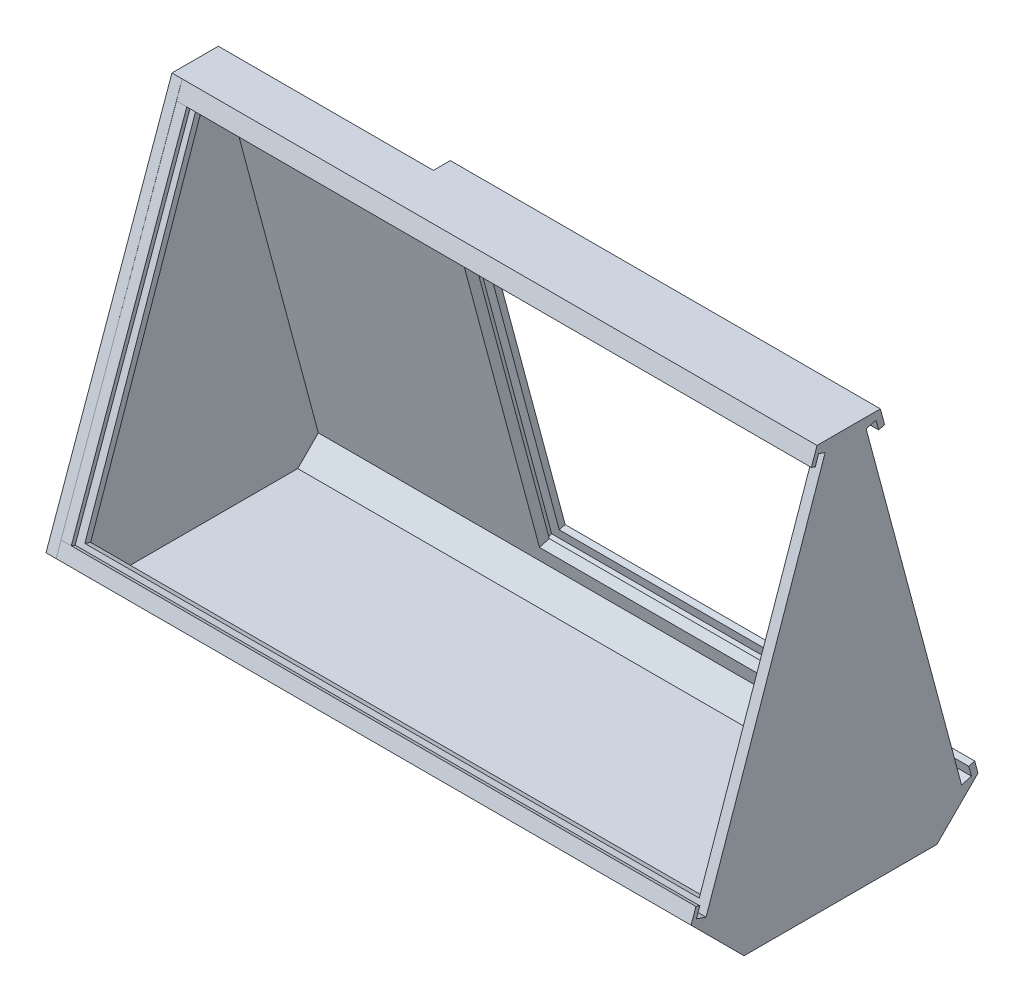
SolidWorks part; units mm, degrees
ref_plane "Front Plane" through (0, 0, 0) normal (0, 0, 1) x (1, 0, 0)
ref_plane "Top Plane" through (0, 0, 0) normal (0, 1, 0) x (1, 0, 0)
ref_plane "Right Plane" through (0, 0, 0) normal (1, 0, 0) x (0, 0, -1)
sketch3d "3DSketch1"
  line L0 (0, 1.3322, 65.6307) -> (0, 1.3322, -48.6693)
  line L1 (0, 19.2927, -66.6298) -> (0, 240.1033, -7.4638)
  line L2 (0, 240.1033, 17.9362) -> (0, 27.5025, 91.801)
  line L3 (0, 1.3322, 65.6307) -> (0, 27.5025, 91.801)
  line L4 (0, 240.1033, 17.9362) -> (0, 240.1033, -7.4638)
  line L5 (0, 19.2927, -66.6298) -> (0, 1.3322, -48.6693)
  point P0 (0, 152.3034, 238.9566)
  dimension "D1" = 25.4
  dimension "D2" = 228.6
  dimension "D3" = 75
  dimension "D4" = 45
  dimension "D5" = 45
  dimension "D6" = 114.3
  dimension "D7" = 225.0669
  dimension "D8" = 25.4
extrude "Boss-Extrude2" add sketch "3DSketch1" along direction (1, 0, 0) on the side of the normal blind 6.35
sketch "Sketch2" plane through (-6.35, 0, 0) normal (-1, 0, 0) x (0, 0, 1)
  line L0 (-61.4451, 14.1079) -> (-48.6693, 1.3322)
  line L1 (-48.6693, 1.3322) -> (65.6307, 1.3322)
  line L2 (65.6307, 1.3322) -> (88.8076, 24.5091)
  line L3 (-71.1199, 27.0698) -> (-74.8001, 28.0559)
  line L4 (-76.8232, 20.5058) -> (-51.2996, -5.0178)
  line L5 (-51.2996, -5.0178) -> (68.261, -5.0178)
  line L6 (68.261, -5.0178) -> (101.1012, 27.8224)
  line L7 (65.6307, 1.3322) -> (91.801, 27.5025) construction
  line L8 (-71.1199, 27.0698) -> (-72.7634, 20.9362)
  line L9 (91.801, 27.5025) -> (97.7993, 29.5865)
  line L10 (-7.4638, 240.1033) -> (-66.6298, 19.2927) construction
  line L11 (-66.6298, 19.2927) -> (-72.7634, 20.9362)
  line L12 (-74.8001, 28.0559) -> (-76.8232, 20.5058)
  line L13 (97.7993, 29.5865) -> (95.7153, 35.5848)
  line L14 (95.7153, 35.5848) -> (98.1146, 36.4184)
  line L15 (98.1146, 36.4184) -> (101.1012, 27.8224)
  line L17 (91.801, 27.5025) -> (17.9362, 240.1033) construction
  line L18 (-66.6298, 19.2927) -> (-64.9863, 25.4263)
  line L19 (-64.9863, 25.4263) -> (-58.8527, 23.7828)
  line L20 (-58.8527, 23.7828) -> (-61.4451, 14.1079)
  line L21 (91.801, 27.5025) -> (89.717, 33.5008)
  line L22 (89.717, 33.5008) -> (86.1181, 32.2504)
  line L23 (86.1181, 32.2504) -> (88.8076, 24.5091)
  dimension "D1" = 6.35
  dimension "D2" = 135
  dimension "D3" = 135
  dimension "D4" = 6.35
  dimension "D5" = 6.35
  dimension "D6" = 6.35
  dimension "D7" = 6.35
  dimension "D8" = 6.35
  dimension "D9" = 3.81
  dimension "D10" = 90
  dimension "D11" = 6.35
  dimension "D12" = 6.35
  dimension "D13" = 2.54
  dimension "D14" = 6.35
  dimension "D15" = 3.81
  dimension "D16" = 6.35
  dimension "D17" = 6.35
extrude "Boss-Extrude3" add sketch "Sketch2" against normal blind 6.35 and the other way blind 254
sketch "Sketch4" plane through (-6.35, 0, 0) normal (-1, 0, 0) x (0, 0, 1)
  line L0 (-0.8898, 240.1033) -> (13.9028, 240.1033)
  line L1 (17.9362, 240.1033) -> (20.0202, 234.105)
  line L2 (89.717, 33.5008) -> (17.9362, 240.1033) construction
  line L3 (16.4213, 232.8546) -> (13.9028, 240.1033)
  line L4 (-7.4638, 240.1033) -> (-13.5974, 241.7468)
  line L5 (-0.8898, 240.1033) -> (-2.9737, 232.3262)
  line L6 (-2.9737, 232.3262) -> (-9.1073, 233.9697)
  line L7 (-7.4638, 240.1033) -> (-64.9863, 25.4263) construction
  line L8 (-9.1073, 233.9697) -> (-7.4638, 240.1033)
  line L9 (16.4213, 232.8546) -> (20.0202, 234.105)
  line L10 (-13.5974, 241.7468) -> (-15.2409, 235.6132)
  line L11 (-15.2409, 235.6132) -> (-18.9211, 236.5993)
  line L12 (-18.9211, 236.5993) -> (-16.2807, 246.4533)
  line L13 (-16.2807, 246.4533) -> (23.001, 246.4533)
  line L14 (23.001, 246.4533) -> (26.5081, 236.3591)
  line L15 (26.5081, 236.3591) -> (24.1087, 235.5255)
  line L16 (24.1087, 235.5255) -> (22.0247, 241.5238)
  line L17 (22.0247, 241.5238) -> (17.9362, 240.1033)
  dimension "D1" = 180
  dimension "D2" = 90
  dimension "D3" = 3.81
  dimension "D4" = 6.35
  dimension "D5" = 6.35
  dimension "D6" = 6.35
  dimension "D7" = 3.81
  dimension "D8" = 6.35
  dimension "D9" = 6.35
  dimension "D10" = 6.35
  dimension "D11" = 90
  dimension "D12" = 270
  dimension "D13" = 6.35
  dimension "D14" = 2.54
  dimension "D15" = 6.35
  dimension "D16" = 3.81
extrude "Boss-Extrude4" add sketch "Sketch4" against normal blind 6.35 and the other way blind 254
sketch "Sketch5" plane through (-260.35, 0, 0) normal (-1, 0, 0) x (0, 0, 1)
  line L0 (-68.5276, 12.2102) -> (-51.2996, -5.0178)
  line L2 (-51.2996, -5.0178) -> (68.261, -5.0178)
  line L3 (68.261, -5.0178) -> (101.1012, 27.8224)
  line L4 (101.1012, 27.8224) -> (98.1146, 36.4184)
  line L5 (95.7153, 35.5848) -> (97.7993, 29.5865)
  line L6 (97.7993, 29.5865) -> (91.801, 27.5025)
  line L7 (91.801, 27.5025) -> (89.717, 33.5008)
  line L8 (89.717, 33.5008) -> (86.1181, 32.2504)
  line L9 (86.1181, 32.2504) -> (88.8076, 24.5091)
  line L10 (88.8076, 24.5091) -> (65.6307, 1.3322)
  line L11 (65.6307, 1.3322) -> (-48.6693, 1.3322)
  line L12 (-48.6693, 1.3322) -> (-61.4451, 14.1079)
  line L13 (-68.5276, 12.2102) -> (-5.7623, 246.4533)
  line L14 (-0.8898, 240.1033) -> (13.9028, 240.1033)
  line L15 (13.9028, 240.1033) -> (16.4213, 232.8546)
  line L16 (16.4213, 232.8546) -> (20.0202, 234.105)
  line L17 (20.0202, 234.105) -> (17.9362, 240.1033)
  line L18 (17.9362, 240.1033) -> (22.0247, 241.5238)
  line L19 (22.0247, 241.5238) -> (24.1087, 235.5255)
  line L20 (24.1087, 235.5255) -> (26.5081, 236.3591)
  line L21 (26.5081, 236.3591) -> (23.001, 246.4533)
  line L22 (23.001, 246.4533) -> (-5.7623, 246.4533)
  line L23 (-0.8898, 240.1033) -> (-61.4451, 14.1079)
  line L44 (-64.9863, 25.4263) -> (-66.6298, 19.2927)
  line L45 (-66.6298, 19.2927) -> (-72.7634, 20.9362)
  line L46 (-72.7634, 20.9362) -> (-71.1199, 27.0698)
  line L47 (-71.1199, 27.0698) -> (-74.8001, 28.0559)
  line L48 (-74.8001, 28.0559) -> (-76.8232, 20.5058)
  line L49 (-76.8232, 20.5058) -> (-51.2996, -5.0178)
  line L50 (-51.2996, -5.0178) -> (68.261, -5.0178)
  line L51 (68.261, -5.0178) -> (101.1012, 27.8224)
  line L52 (101.1012, 27.8224) -> (98.1146, 36.4184)
  line L53 (98.1146, 36.4184) -> (95.7153, 35.5848)
  line L54 (95.7153, 35.5848) -> (97.7993, 29.5865)
  line L55 (97.7993, 29.5865) -> (91.801, 27.5025)
  line L56 (91.801, 27.5025) -> (89.717, 33.5008)
  line L57 (89.717, 33.5008) -> (86.1181, 32.2504)
  line L58 (86.1181, 32.2504) -> (88.8076, 24.5091)
  line L59 (88.8076, 24.5091) -> (65.6307, 1.3322)
  line L60 (65.6307, 1.3322) -> (-48.6693, 1.3322)
  line L61 (-48.6693, 1.3322) -> (-61.4451, 14.1079)
  line L62 (-61.4451, 14.1079) -> (-58.8527, 23.7828)
  line L63 (-58.8527, 23.7828) -> (-64.9863, 25.4263)
  line L73 (98.1146, 36.4184) -> (95.7153, 35.5848)
  dimension "D1" = 0
extrude "Boss-Extrude5" add sketch "Sketch5" along normal blind 133.35
sketch "Sketch7" plane through (-260.35, 0, 0) normal (-1, 0, 0) x (0, 0, 1)
  line L0 (-16.2807, 246.4533) -> (-76.8232, 20.5058)
  line L1 (-76.8232, 20.5058) -> (-68.5276, 12.2102)
  line L2 (-68.5276, 12.2102) -> (-5.7623, 246.4533)
  line L3 (-5.7623, 246.4533) -> (-16.2807, 246.4533)
extrude "Boss-Extrude6" add sketch "Sketch7" along normal blind 6.35
sketch "Sketch9" plane through (-260.35, 0, 0) normal (1, 0, 0) x (0, 0, -1)
  line L0 (15.2409, 235.6132) -> (71.1199, 27.0698)
  line L1 (71.1199, 27.0698) -> (74.8001, 28.0559)
  line L2 (74.8001, 28.0559) -> (18.9211, 236.5993)
  line L3 (18.9211, 236.5993) -> (15.2409, 235.6132)
  line L4 (2.9737, 232.3262) -> (9.1073, 233.9697)
  line L5 (9.1073, 233.9697) -> (64.9863, 25.4263)
  line L6 (64.9863, 25.4263) -> (58.8527, 23.7828)
  line L7 (58.8527, 23.7828) -> (2.9737, 232.3262)
extrude "Boss-Extrude8" add sketch "Sketch9" along normal blind 6.35
sketch "Sketch11" plane through (-393.7, 0, 0) normal (-1, 0, 0) x (0, 0, 1)
  line L0 (23.001, 246.4533) -> (101.1012, 27.8224)
  line L1 (101.1012, 27.8224) -> (68.261, -5.0178)
  line L2 (23.001, 246.4533) -> (-5.7623, 246.4533)
  line L3 (-5.7623, 246.4533) -> (-68.5276, 12.2102)
  line L4 (-68.5276, 12.2102) -> (-51.2996, -5.0178)
  line L5 (-51.2996, -5.0178) -> (68.261, -5.0178)
extrude "Boss-Extrude9" add sketch "Sketch11" along normal blind 6.35
sketch "Sketch12" plane through (-393.7, 0, 0) normal (1, 0, 0) x (0, 0, -1)
  line L0 (-24.1087, 235.5255) -> (-26.5081, 236.3591)
  line L1 (-26.5081, 236.3591) -> (-98.1146, 36.4184)
  line L2 (-98.1146, 36.4184) -> (-95.7153, 35.5848)
  line L3 (-95.7153, 35.5848) -> (-24.1087, 235.5255)
  line L4 (-20.0202, 234.105) -> (-16.4213, 232.8546)
  line L5 (-16.4213, 232.8546) -> (-86.1181, 32.2504)
  line L6 (-86.1181, 32.2504) -> (-89.717, 33.5008)
  line L7 (-89.717, 33.5008) -> (-20.0202, 234.105)
extrude "Boss-Extrude10" add sketch "Sketch12" along normal blind 6.35
